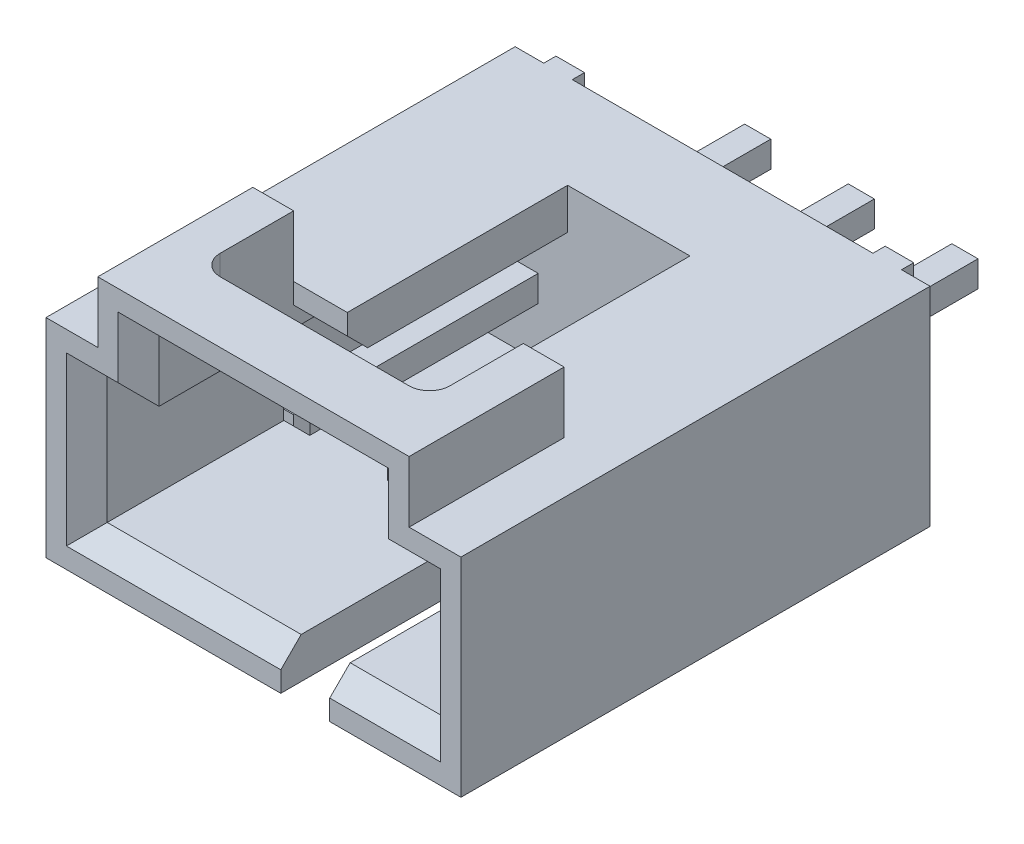
SolidWorks part; units mm, degrees
ref_plane "Front" through (0, 0, 0) normal (0, 0, 1) x (1, 0, 0)
ref_plane "Top" through (0, 0, 0) normal (0, 1, 0) x (1, 0, 0)
ref_plane "Right" through (0, 0, 0) normal (1, 0, 0) x (0, 0, -1)
sketch "Эскиз1" plane through (0, 0, 0) normal (0, 1, 0) x (1, 0, 0)
  line L0 (-3.685, -0.3) -> (3.685, -0.3)
  line L1 (3.685, -0.3) -> (3.685, 0)
  line L2 (3.685, 0) -> (4.385, 0)
  line L3 (4.385, 0) -> (4.385, -0.3)
  line L4 (4.385, -0.3) -> (5.085, -0.3)
  line L5 (5.085, -0.3) -> (5.085, -11.8)
  line L6 (5.085, -11.8) -> (-5.085, -11.8)
  line L7 (-5.085, -11.8) -> (-5.085, -0.3)
  line L8 (-5.085, -0.3) -> (-4.385, -0.3)
  line L9 (-4.385, -0.3) -> (-4.385, 0)
  line L10 (-4.385, 0) -> (-3.685, 0)
  line L11 (-3.685, 0) -> (-3.685, -0.3)
  line L12 (0, -0.3) -> (0, 0) construction
  line L13 (0, -11.8) -> (0, -0.3) construction
  point P16 (9.6929, -12.8334)
  point P17 (0, 0)
  point P18 (-3.4521, 0)
  point P19 (-2.5299, 0)
  point P20 (3.1228, 0)
  point P21 (-3.81, -0.9794)
  dimension "D2" = 10.17
  dimension "D3" = 0.7
  dimension "D1" = 11.8
  dimension "D4" = 0.3
  dimension "D5" = 0.7
extrude "Бобышка-Вытянуть1" add sketch "Эскиз1" along normal mid plane 5.1
sketch "Эскиз2" plane through (0, 0, 11.8) normal (0, 0, 1) x (1, 0, 0)
  line L0 (-4.085, 1.55) -> (-4.085, -1.55)
  line L2 (4.085, -1.55) -> (4.085, 1.55)
  line L3 (4.085, 1.55) -> (1.5, 1.55)
  line L4 (1.5, 1.55) -> (1.5, 2.55)
  line L6 (1.5, 2.55) -> (-1.5, 2.55)
  line L7 (-1.5, 2.55) -> (-1.5, 1.55)
  line L8 (-1.5, 1.55) -> (-4.085, 1.55)
  line L9 (4.085, -1.55) -> (1.87, -1.55)
  line L10 (1.87, -1.55) -> (1.87, -2.55)
  line L11 (-5.085, -2.55) -> (5.085, -2.55) construction
  line L12 (1.87, -2.55) -> (0.67, -2.55)
  line L13 (0.67, -2.55) -> (0.67, -1.55)
  line L14 (0.67, -1.55) -> (-4.085, -1.55)
  line L15 (4.085, 1.55) -> (5.085, 1.55) construction
  line L16 (5.085, 2.55) -> (5.085, -2.55) construction
  line L17 (-4.085, 1.55) -> (-5.085, 1.55) construction
  line L18 (-5.085, 2.55) -> (-5.085, -2.55) construction
  line L19 (-5.085, 2.55) -> (5.085, 2.55) construction
  point P7 (0, 2.55)
  point P8 (0, 2.55)
  point P20 (1.27, -2.55)
  point P23 (0, 0)
  dimension "D1" = 1.2
  dimension "D2" = 3
  dimension "D3" = 1
  dimension "D4" = 3.815
extrude "Вырез-Вытянуть1" cut sketch "Эскиз2" against normal offset from surface (9.2 mm away) 2.3 up to face at (0, 0, 0.3)
sketch "Эскиз3" plane through (0, 0, 11.8) normal (0, 0, 1) x (1, 0, 0)
  line L0 (-3.815, 2.55) -> (-3.815, 4.05)
  line L1 (-5.085, 2.55) -> (-1.5, 2.55) construction
  line L2 (-3.815, 4.05) -> (3.815, 4.05)
  line L3 (3.815, 4.05) -> (3.815, 2.55)
  line L5 (3.815, 2.55) -> (2.815, 2.55)
  line L6 (2.815, 2.55) -> (2.815, 3.05)
  line L7 (2.815, 3.05) -> (-2.815, 3.05)
  line L8 (-2.815, 3.05) -> (-2.815, 2.55)
  line L9 (-2.815, 2.55) -> (-3.815, 2.55)
  line L10 (0, 0) -> (0, 3.05) construction
  line L11 (0, 3.05) -> (0, 4.05) construction
  line L12 (2.815, 1.55) -> (2.815, 2.55) construction
  line L15 (1.5, 2.55) -> (5.085, 2.55) construction
  line L16 (4.085, 1.55) -> (1.5, 1.55) construction
  line L17 (1.87, -2.55) -> (5.085, -2.55) construction
  point P7 (2.7781, 2.55)
  point P17 (2.5332, 1.55)
  point P18 (3.2925, 2.55)
  point P19 (3.2925, 2.55)
  point P20 (2.2925, 3.387)
  point P22 (4.0188, 2.55)
  point P23 (2.6084, 1.55)
  point P26 (3.908, 2.55)
  dimension "D1" = 7.63
  dimension "D2" = 6.6
extrude "Бобышка-Вытянуть2" add sketch "Эскиз3" against normal blind 3.8
sketch "Эскиз4" plane through (0, 0, 11.8) normal (0, 0, 1) x (1, 0, 0)
  line L0 (-2.815, 2.55) -> (-2.815, 1.55)
  line L1 (-1.5, 1.55) -> (-4.085, 1.55) construction
  line L2 (-2.815, 1.55) -> (2.815, 1.55)
  line L3 (4.085, 1.55) -> (1.5, 1.55) construction
  line L4 (2.815, 1.55) -> (2.815, 2.55)
  line L5 (2.815, 2.55) -> (-2.815, 2.55)
extrude "Вырез-Вытянуть2" cut sketch "Эскиз4" against normal up to surface (3.8 mm away) up to face at (0, 3.05, 8)
sketch "Эскиз5" plane through (0, 4.05, 0) normal (0, 1, 0) x (1, 0, 0)
  line L0 (2.815, -8) -> (2.815, -9.8)
  line L1 (3.815, -8) -> (-3.815, -8) construction
  line L2 (2.315, -10.3) -> (-2.315, -10.3)
  line L3 (-2.815, -9.8) -> (-2.815, -8)
  line L4 (-2.815, -8) -> (2.815, -8)
  line L5 (3.815, -11.8) -> (-3.815, -11.8) construction
  arc A0 (2.815, -9.8) -> (2.315, -10.3) centre (2.315, -9.8) cw
  arc A1 (-2.315, -10.3) -> (-2.815, -9.8) centre (-2.315, -9.8) cw
  point P9 (0, 0)
  point P11 (0, 0)
  point P14 (-2.4442, -11.0462)
  dimension "D1" = 1.5
  dimension "D2" = 0.5
extrude "Вырез-Вытянуть3" cut sketch "Эскиз5" against normal up to next
chamfer "Фаска1" distance 0.5 angle 45 11 edges at (2.9775, -1.55, 11.8) (4.085, 0, 11.8) (3.45, 1.55, 11.8) (2.815, 2.3, 11.8) (-1.7075, -1.55, 11.8) (-4.085, 0, 11.8) (-3.45, 1.55, 11.8) (-2.815, 2.3, 11.8) (0, 3.05, 11.8) (-2.1575, 1.55, 8) (2.1575, 1.55, 8)
sketch "Эскиз6" plane through (0, 0, 0.3) normal (0, 0, 1) x (1, 0, 0)
  line L0 (0, 0) -> (2.54, 0) construction
  line L1 (2.86, -0.32) -> (2.22, -0.32)
  line L2 (2.86, -0.32) -> (2.86, 0.32)
  line L3 (2.86, 0.32) -> (2.22, 0.32)
  line L4 (2.22, -0.32) -> (2.22, 0.32)
  line L5 (2.86, -0.32) -> (2.22, 0.32) construction
  line L6 (2.86, 0.32) -> (2.22, -0.32) construction
  line L7 (5.085, 2.55) -> (5.085, -2.55) construction
  point P0 (2.54, 0)
  point P10 (0, 0)
  dimension "D1" = 0.64
  dimension "D2" = 0.64
  dimension "D3" = 2.545
extrude "Бобышка-Вытянуть3" add sketch "Эскиз6" along normal offset from surface 3.4 and the other way offset from surface (3.6 mm away) 3.3 up to face at (0.254, 0.76, 11.8) other way up to face at (4.035, 0, 0)
chamfer "Фаска2" distance 0.2 angle 45 8 edges at (2.22, 0, 8.4) (2.54, 0.32, 8.4) (2.86, 0, 8.4) (2.54, -0.32, 8.4) (2.54, -0.32, -3.3) (2.86, 0, -3.3) (2.54, 0.32, -3.3) (2.22, 0, -3.3)
pattern_linear "Линейный массив1" count 3 spacing 2.54 along (-1, 0, 0) of "Бобышка-Вытянуть3", "Фаска2"
equation "\"Pins\"= 3"
equation "\"B\"= \"Pins\" * 2.54мм + 2.55мм"
equation "\"D2@Эскиз1\"= \"B\""
equation "\"D1@Линейный массив1\"= \"Pins\""
